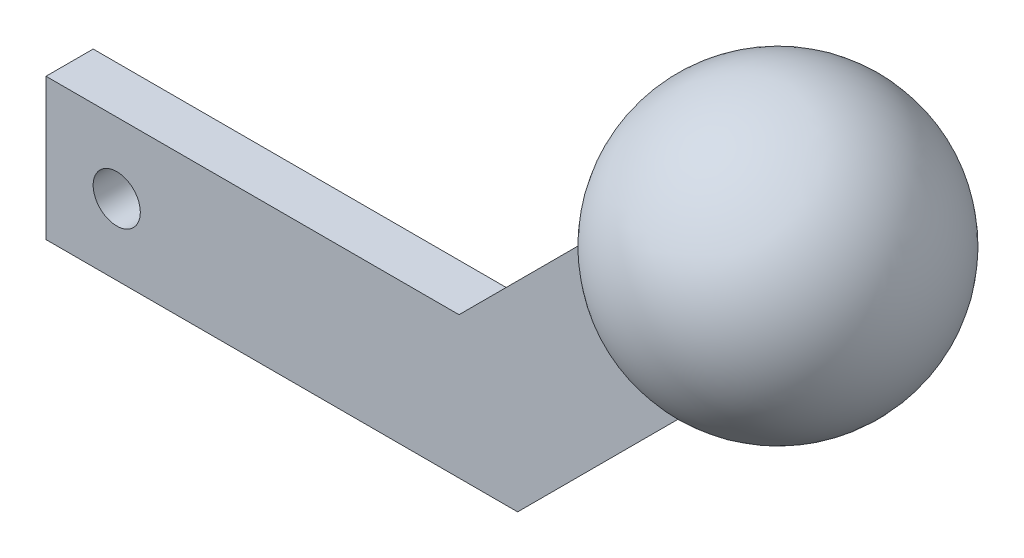
SolidWorks part; units mm, degrees
ref_plane "Front Plane" through (0, 0, 0) normal (0, 0, 1) x (1, 0, 0)
ref_plane "Top Plane" through (0, 0, 0) normal (0, 1, 0) x (1, 0, 0)
ref_plane "Right Plane" through (0, 0, 0) normal (1, 0, 0) x (0, 0, -1)
sketch "Sketch1" plane through (0, 0, 0) normal (0, 0, 1) x (1, 0, 0)
  line L0 (0, 0) -> (50, 0)
  line L1 (50, 0) -> (71.2132, 21.2132)
  line L2 (71.2132, 21.2132) -> (60.6066, 31.8198)
  line L3 (60.6066, 31.8198) -> (43.7868, 15)
  line L4 (43.7868, 15) -> (0, 15)
  line L5 (0, 15) -> (0, 0)
  circle A0 centre (7.5, 7.5) radius 2.5
  dimension "D6" = 7.5
  dimension "D7" = 7.5
  dimension "D8" = 5
  dimension "D1" = 15
  dimension "D2" = 15
  dimension "D3" = 135
  dimension "D4" = 50
  dimension "D5" = 30
extrude "Boss-Extrude1" add sketch "Sketch1" along normal blind 5
ref_plane "Plane1" through (0, 0, 2.5) normal (0, 0, 1) x (1, 0, 0)
sketch "Sketch2" plane through (0, 0, 2.5) normal (0, 0, 1) x (1, 0, 0)
  line L0 (71.2132, 21.2132) -> (60.6066, 31.8198) construction
  line L1 (71.2132, 21.2132) -> (65.9099, 26.5165) construction
  line L2 (65.9099, 26.5165) -> (85.7021, 46.3087)
  line L3 (65.9099, 26.5165) -> (71.2132, 21.2132)
  line L4 (71.2132, 21.2132) -> (60.6066, 31.8198) construction
  arc A0 (85.7021, 46.3087) -> (71.2132, 21.2132) centre (75.0955, 35.7021) cw
  point P0 (65.9099, 26.5165)
  point P2 (68.5616, 23.8649)
  dimension "D1" = 15
revolve "Revolve2" add sketch "Sketch2" angle 360 about L2
